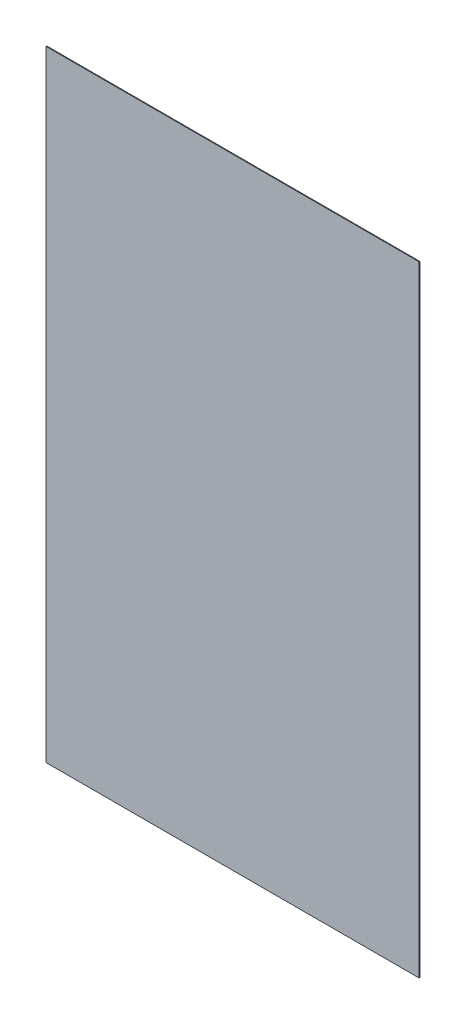
SolidWorks part; units mm, degrees
material "Glass"
ref_plane "Front Plane" through (0, 0, 0) normal (0, 0, 1) x (1, 0, 0)
ref_plane "Top Plane" through (0, 0, 0) normal (0, 1, 0) x (1, 0, 0)
ref_plane "Right Plane" through (0, 0, 0) normal (1, 0, 0) x (0, 0, -1)
sketch "Sketch1" plane through (0, 0, 0) normal (0, 0, 1) x (1, 0, 0)
  line L1 (0, 0) -> (1000, 0)
  line L2 (0, 0) -> (0, 1662.9)
  line L3 (0, 1662.9) -> (1000, 1662.9)
  line L4 (1000, 0) -> (1000, 1662.9)
  dimension "D1" = 1000
  dimension "D2" = 1662.9
extrude "Boss-Extrude1" add sketch "Sketch1" along normal blind 2
